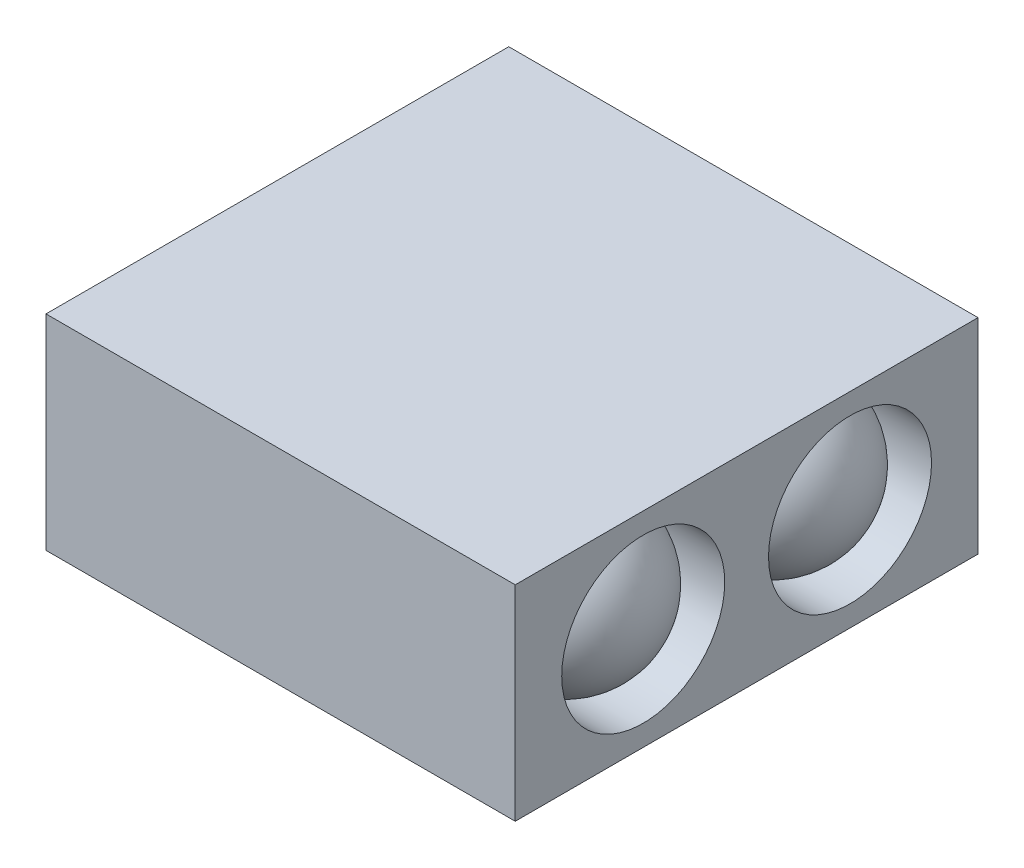
SolidWorks part; units mm, degrees
ref_plane "Front Plane" through (0, 0, 0) normal (0, 0, 1) x (1, 0, 0)
ref_plane "Top Plane" through (0, 0, 0) normal (0, 1, 0) x (1, 0, 0)
ref_plane "Right Plane" through (0, 0, 0) normal (1, 0, 0) x (0, 0, -1)
sketch "Sketch1" plane through (0, 0, 0) normal (0, 1, 0) x (1, 0, 0)
  line L1 (-181, -178.5) -> (181, -178.5)
  line L2 (-181, -178.5) -> (-181, 178.5)
  line L3 (-181, 178.5) -> (181, 178.5)
  line L4 (181, -178.5) -> (181, 178.5)
  line L5 (-181, -178.5) -> (181, 178.5) construction
  line L6 (-181, 178.5) -> (181, -178.5) construction
  point P0 (0, 0)
  dimension "D1" = 357
  dimension "D2" = 362
extrude "Boss-Extrude1" add sketch "Sketch1" along normal blind 158
sketch "Sketch2" plane through (181, 0, 0) normal (1, 0, 0) x (0, 0, -1)
  line L0 (-178.5, 79) -> (178.5, 79) construction
  line L1 (-178.5, 158) -> (-178.5, 0) construction
  line L2 (178.5, 158) -> (178.5, 0) construction
  line L3 (0, 158) -> (0, 0) construction
  line L4 (-178.5, 158) -> (178.5, 158) construction
  circle A0 centre (-79.774, 79) radius 62.8771
  circle A1 centre (79.774, 79) radius 62.8771
extrude "Cut-Extrude1" cut sketch "Sketch2" against normal blind 60
sketch "Sketch3" plane through (121, 0, 0) normal (1, 0, 0) x (0, 0, -1)
  line L0 (-79.774, 141.8771) -> (-79.774, 16.1229)
  arc A0 (-79.774, 141.8771) -> (-79.774, 16.1229) centre (-79.774, 79) ccw
revolve "Revolve1" add sketch "Sketch3" angle 180 about L0
sketch "Sketch4" plane through (121, 0, 0) normal (1, 0, 0) x (0, 0, -1)
  line L0 (79.774, 141.8771) -> (79.774, 16.1229)
  arc A0 (79.774, 141.8771) -> (79.774, 16.1229) centre (79.774, 79) ccw
revolve "Revolve2" add sketch "Sketch4" angle 180 about L0
